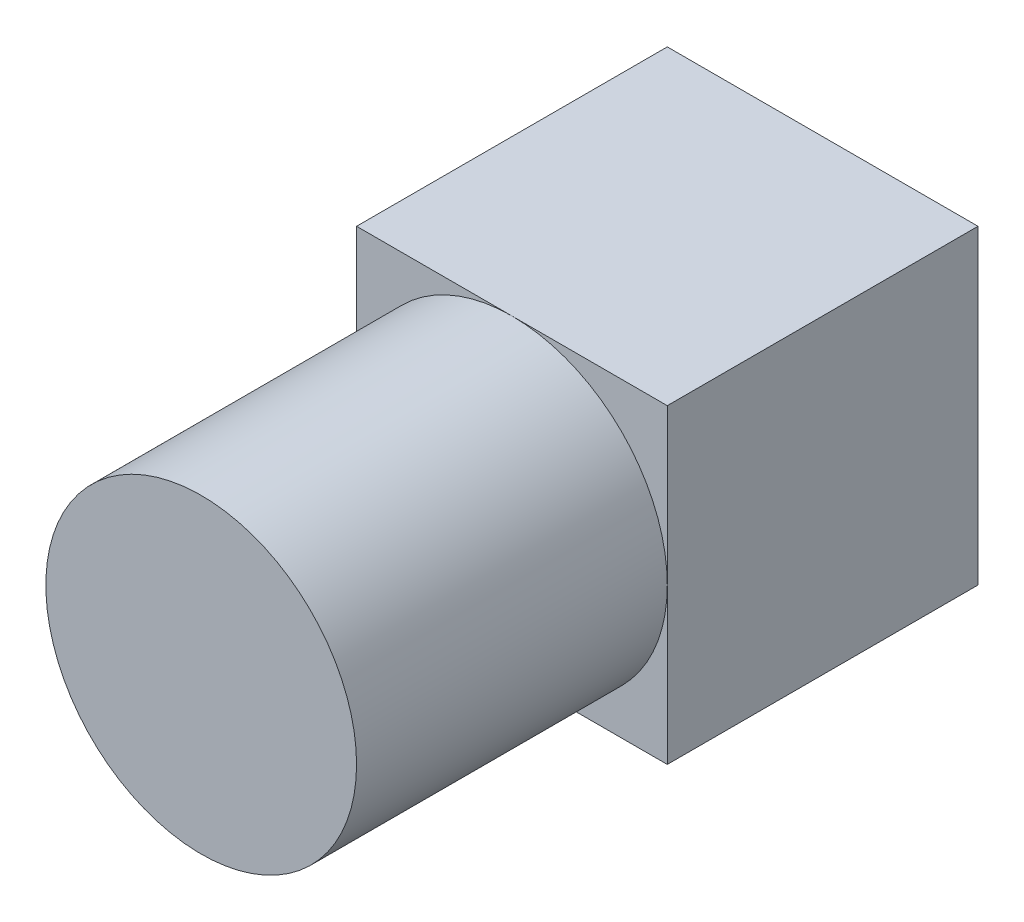
SolidWorks part; units mm, degrees
ref_plane "Front Plane" through (0, 0, 0) normal (0, 0, 1) x (1, 0, 0)
ref_plane "Top Plane" through (0, 0, 0) normal (0, 1, 0) x (1, 0, 0)
ref_plane "Right Plane" through (0, 0, 0) normal (1, 0, 0) x (0, 0, -1)
sketch "Sketch1" plane through (0, 0, 0) normal (0, 0, 1) x (1, 0, 0)
  line L1 (-1.27, 1.27) -> (1.27, 1.27)
  line L2 (-1.27, 1.27) -> (-1.27, -1.27)
  line L3 (-1.27, -1.27) -> (1.27, -1.27)
  line L4 (1.27, 1.27) -> (1.27, -1.27)
  line L5 (-1.27, 1.27) -> (1.27, -1.27) construction
  line L6 (-1.27, -1.27) -> (1.27, 1.27) construction
  point P0 (0, 0)
  dimension "D1" = 2.54
extrude "Boss-Extrude1" add sketch "Sketch1" against normal blind 2.54
sketch "Sketch2" plane through (0, 0, 0) normal (0, 0, 1) x (1, 0, 0)
  circle A0 centre (0, 0) radius 1.27
extrude "Boss-Extrude2" add sketch "Sketch2" along normal blind 2.54
